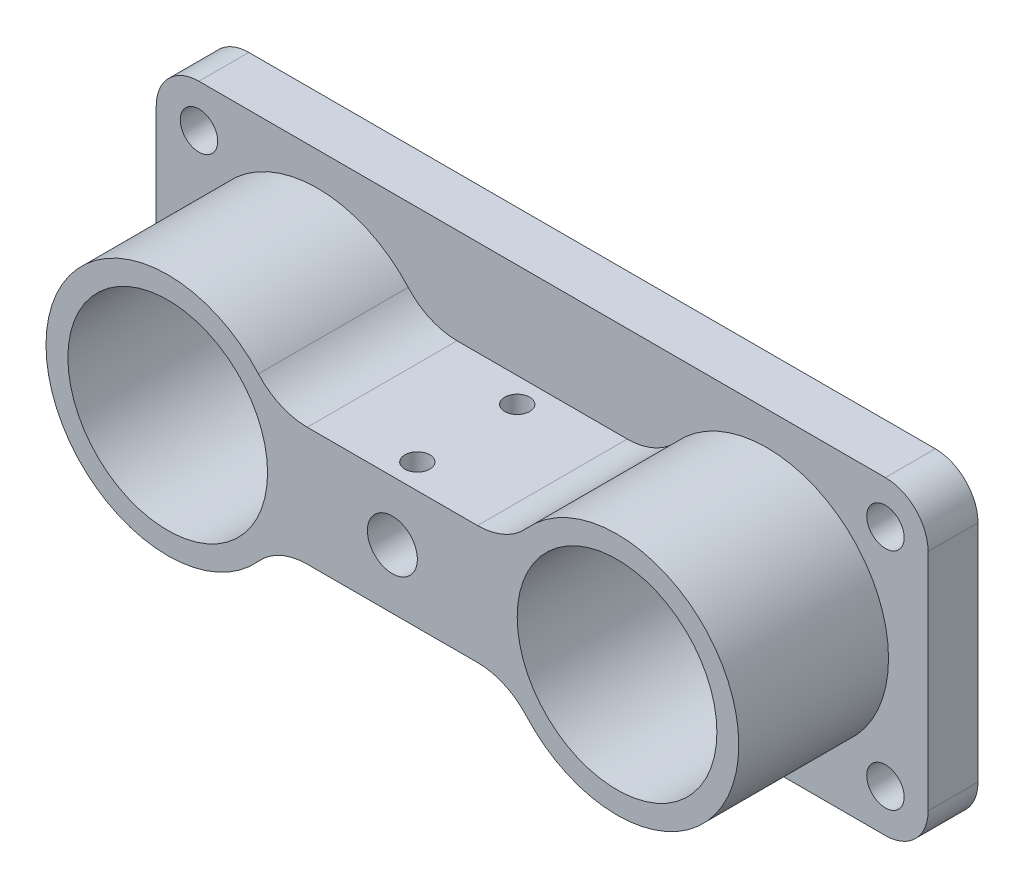
SolidWorks part; units mm, degrees
ref_plane "front" through (0, 0, 0) normal (0, 0, 1) x (1, 0, 0)
ref_plane "top" through (0, 0, 0) normal (0, 1, 0) x (1, 0, 0)
ref_plane "right" through (0, 0, 0) normal (1, 0, 0) x (0, 0, -1)
sketch "Sketch7" plane through (0, 0, 0) normal (0, 0, 1) x (1, 0, 0)
  line L0 (87.3125, 39.4335) -> (-87.3125, 39.4335)
  line L1 (-98.171, 28.575) -> (-98.171, -28.575)
  line L2 (-87.3125, -39.4335) -> (87.3125, -39.4335)
  line L3 (98.171, -28.575) -> (98.171, 28.575)
  line L5 (-85.2165, -36.5641) -> (-79.3394, -30.7654) construction
  line L6 (-79.3394, -30.7654) -> (-81.4227, -22.7763) construction
  line L7 (-81.4227, -22.7763) -> (-89.3831, -20.5859) construction
  line L8 (-89.3831, -20.5859) -> (-95.2602, -26.3846) construction
  line L9 (-95.2602, -26.3846) -> (-93.1769, -34.3737) construction
  line L10 (-93.1769, -34.3737) -> (-85.2165, -36.5641) construction
  arc A0 (87.3125, 39.4335) -> (98.171, 28.575) centre (87.3125, 28.575) cw
  circle A1 centre (-57.15, 0) radius 25.4
  circle A2 centre (-87.2998, -28.575) radius 10.3187 construction
  circle A3 centre (-87.2998, -28.575) radius 7.1501 construction
  arc A4 (-87.3125, 39.4335) -> (-98.171, 28.575) centre (-87.3125, 28.575) ccw
  arc A5 (-98.171, -28.575) -> (-87.3125, -39.4335) centre (-87.3125, -28.575) ccw
  arc A6 (87.3125, -39.4335) -> (98.171, -28.575) centre (87.3125, -28.575) ccw
  circle A8 centre (-87.2998, -28.575) radius 4.7625
  circle A9 centre (-87.2998, 28.575) radius 4.7625
  circle A10 centre (87.3252, -28.575) radius 4.7625
  circle A11 centre (87.3252, 28.575) radius 4.7625
  circle A12 centre (0, 0) radius 6.35
  circle A13 centre (57.15, 0) radius 25.4
  point P26 (98.171, 0)
  point P27 (0, 39.4335)
  dimension "D1" = 10.8585
  dimension "D6" = 50.8
  dimension "D7" = 12.7
  dimension "D12" = 9.525
  dimension "D13" = 20.6375
  dimension "D14" = 14.3002
  dimension "D2" = 196.342
  dimension "D3" = 78.867
  dimension "D4" = 57.15
  dimension "D5" = 57.15
  dimension "D8" = 87.3252
  dimension "D9" = 174.625
  dimension "D10" = 28.575
  dimension "D11" = 57.15
  dimension "D15" = 185.4835
  dimension "D16" = 10.8585
sketch "Sketch1" plane through (0, 0, 0) normal (0, 0, 1) x (1, 0, 0)
  line L12 (99.7585, -28.575) -> (99.7585, 28.575)
  line L13 (87.3125, 41.021) -> (-87.3125, 41.021)
  line L14 (-99.7585, 28.575) -> (-99.7585, -28.575)
  line L15 (-87.3125, -41.021) -> (87.3125, -41.021)
  line L16 (99.7585, -28.575) -> (99.7585, 28.575)
  line L17 (87.3125, 41.021) -> (-87.3125, 41.021)
  line L18 (-99.7585, 28.575) -> (-99.7585, -28.575)
  line L19 (-87.3125, -41.021) -> (87.3125, -41.021)
  arc A18 (99.7585, 28.575) -> (87.3125, 41.021) centre (87.3125, 28.575) ccw
  arc A19 (-87.3125, 41.021) -> (-99.7585, 28.575) centre (-87.3125, 28.575) ccw
  arc A20 (-99.7585, -28.575) -> (-87.3125, -41.021) centre (-87.3125, -28.575) ccw
  arc A21 (87.3125, -41.021) -> (99.7585, -28.575) centre (87.3125, -28.575) ccw
  arc A22 (99.7585, 28.575) -> (87.3125, 41.021) centre (87.3125, 28.575) ccw
  arc A23 (-87.3125, 41.021) -> (-99.7585, 28.575) centre (-87.3125, 28.575) ccw
  arc A24 (-99.7585, -28.575) -> (-87.3125, -41.021) centre (-87.3125, -28.575) ccw
  arc A25 (87.3125, -41.021) -> (99.7585, -28.575) centre (87.3125, -28.575) ccw
  dimension "D1" = 1.5875
extrude "Base-Extrude" add sketch "Sketch1" against normal blind 50.8 draft 3
sketch "Sketch8" plane through (0, 0, 0) normal (0, 0, 1) x (1, 0, 0)
  line L0 (25.2111, 29.9085) -> (-25.2111, 29.9085)
  line L1 (-25.2111, -29.9085) -> (25.2111, -29.9085)
  line L2 (87.3125, 39.4335) -> (-87.3125, 39.4335) construction
  line L3 (-87.3125, -39.4335) -> (87.3125, -39.4335) construction
  line L4 (25.2111, 23.5585) -> (-0.1889, 23.5585) construction
  arc A0 (25.2111, -29.9085) -> (30.3213, -19.7891) centre (25.2111, -23.5585) ccw
  arc A1 (25.2111, 29.9085) -> (30.3213, 19.7891) centre (25.2111, 23.5585) cw
  arc A2 (-25.2111, 29.9085) -> (-30.3213, 19.7891) centre (-25.2111, 23.5585) ccw
  arc A3 (-25.2111, -29.9085) -> (-30.3213, -19.7891) centre (-25.2111, -23.5585) cw
  circle A4 centre (0, 0) radius 12.7 construction
  arc A6 (30.3213, 19.7891) -> (30.3213, -19.7891) centre (57.15, 0) ccw
  arc A7 (-30.3213, -19.7891) -> (-30.3213, 19.7891) centre (-57.15, 0) ccw
  dimension "D3" = 66.675
  dimension "D4" = 66.675
  dimension "D5" = 6.35
  dimension "D6" = 25.4
  dimension "D1" = 9.525
  dimension "D2" = 9.525
  dimension "D7" = 25.4
sketch "Sketch17" plane through (0, 0, 0) normal (0, 0, 1) x (1, 0, 0)
  line L0 (25.2111, 23.5585) -> (-0.1889, 23.5585) construction
  line L1 (-25.2111, -29.9085) -> (25.2111, -29.9085) construction
  line L2 (25.2111, 29.9085) -> (-25.2111, 29.9085) construction
  line L3 (25.2111, 23.5585) -> (-0.1889, 23.5585) construction
  line L4 (-25.2111, -29.9085) -> (25.2111, -29.9085)
  line L5 (25.2111, 29.9085) -> (-25.2111, 29.9085)
  line L6 (98.171, -28.575) -> (98.171, 28.575) construction
  line L7 (87.3125, 39.4335) -> (-87.3125, 39.4335) construction
  line L8 (98.171, -28.575) -> (98.171, 28.575)
  line L9 (87.3125, 39.4335) -> (-87.3125, 39.4335)
  line L10 (-25.3525, -20.3835) -> (19.4445, -20.3835) construction
  circle A0 centre (0, 0) radius 12.7 construction
  arc A1 (30.3213, 19.7891) -> (25.2111, 29.9085) centre (25.2111, 23.5585) ccw construction
  arc A2 (30.3213, 19.7891) -> (30.3213, -19.7891) centre (57.15, 0) ccw construction
  arc A3 (25.2111, -29.9085) -> (30.3213, -19.7891) centre (25.2111, -23.5585) ccw construction
  arc A4 (-30.3213, -19.7891) -> (-25.2111, -29.9085) centre (-25.2111, -23.5585) ccw construction
  arc A5 (-30.3213, -19.7891) -> (-30.3213, 19.7891) centre (-57.15, 0) ccw construction
  arc A6 (-25.2111, 29.9085) -> (-30.3213, 19.7891) centre (-25.2111, 23.5585) ccw construction
  circle A7 centre (0, 0) radius 12.7 construction
  arc A8 (30.3213, 19.7891) -> (25.2111, 29.9085) centre (25.2111, 23.5585) ccw
  arc A9 (30.3213, 19.7891) -> (30.3213, -19.7891) centre (57.15, 0) ccw
  arc A10 (25.2111, -29.9085) -> (30.3213, -19.7891) centre (25.2111, -23.5585) ccw
  arc A11 (-30.3213, -19.7891) -> (-25.2111, -29.9085) centre (-25.2111, -23.5585) ccw
  arc A12 (-30.3213, -19.7891) -> (-30.3213, 19.7891) centre (-57.15, 0) ccw
  arc A13 (-25.2111, 29.9085) -> (-30.3213, 19.7891) centre (-25.2111, 23.5585) ccw
  circle A14 centre (0, 0) radius 22.225 construction
  arc A15 (22.8087, 25.6489) -> (19.4445, -20.3835) centre (57.15, 0) ccw construction
  circle A16 centre (0, 0) radius 17.4752
  point P23 (0, -12.7)
  point P24 (0, -22.225)
  point P28 (0, -17.4752)
  point P30 (0, 17.4752)
  dimension "D7" = 6.35
  dimension "D8" = 33.3375
  dimension "D1" = 72.9599
  dimension "D2" = 15.875
  dimension "D3" = 9.525
  dimension "D4" = 67.8497
  dimension "D5" = 15.875
  dimension "D6" = 123.3821
  dimension "D9" = 59.2226
  dimension "D10" = 69.342
  dimension "D11" = 26.8287
  dimension "D12" = 19.7891
  dimension "D13" = 19.6444
  dimension "D14" = 9.525
  dimension "D17" = 98.3599
  dimension "D18" = 128.4923
  dimension "D19" = 3.7694
  dimension "D20" = 5.1102
  dimension "D21" = 6.35
  dimension "D22" = 6.35
  dimension "D23" = 3.7694
  dimension "D24" = 4.7752
  dimension "D25" = 21.9583
  dimension "D26" = 17.4752
  dimension "D15" = 9.525
  dimension "D16" = 9.525
sketch "Sketch2" plane through (0, 0, 0) normal (0, 0, 1) x (1, 0, 0)
  line L0 (0, -2.2818) -> (0, 10.4027) construction
  line L1 (-10.1716, 0) -> (10.1716, 0) construction
  line L2 (-21.6524, 19.05) -> (21.6524, 19.05)
  line L3 (-21.6524, -19.05) -> (21.6524, -19.05)
  line L4 (-99.2711, -9.525) -> (-116.0701, -9.525) construction
  line L5 (-99.2711, 9.525) -> (-116.0701, 9.525) construction
  line L6 (99.2711, -9.525) -> (116.0701, -9.525) construction
  line L7 (99.2711, 9.525) -> (116.0701, 9.525) construction
  line L9 (-124.922, 63.0143) -> (120.2967, 63.0143)
  line L10 (-124.922, 63.0143) -> (-124.922, -70.9973)
  line L11 (-124.922, -70.9973) -> (120.2967, -70.9973)
  line L12 (120.2967, 63.0143) -> (120.2967, -70.9973)
  arc A0 (31.1184, -23.2833) -> (31.1184, 23.2833) centre (57.15, 0) ccw
  arc A1 (-31.1184, 23.2833) -> (-31.1184, -23.2833) centre (-57.15, 0) ccw
  circle A2 centre (0, 0) radius 15.875 construction
  circle A3 centre (0, 0) radius 8.7376 construction
  circle A4 centre (15.4813, 0) radius 6.7437 construction
  arc A5 (21.6524, 19.05) -> (31.1184, 23.2833) centre (21.6524, 31.75) ccw
  arc A6 (-21.6524, 19.05) -> (-31.1184, 23.2833) centre (-21.6524, 31.75) cw
  arc A7 (-21.6524, -19.05) -> (-31.1184, -23.2833) centre (-21.6524, -31.75) ccw
  arc A8 (21.6524, -19.05) -> (31.1184, -23.2833) centre (21.6524, -31.75) cw
  circle A9 centre (-87.2998, -28.575) radius 10.3188 construction
  circle A10 centre (-87.2998, -28.575) radius 10.3187 construction
  arc A11 (-87.207, -18.2567) -> (-99.2711, -9.525) centre (-99.2711, -22.225) ccw construction
  arc A12 (-88.0388, 16.2983) -> (-99.2711, 9.525) centre (-99.2711, 22.225) cw construction
  arc A13 (87.207, -18.2567) -> (99.2711, -9.525) centre (99.2711, -22.225) cw construction
  arc A14 (88.0388, 16.2983) -> (99.2711, 9.525) centre (99.2711, 22.225) ccw construction
  dimension "D1" = 69.85
  dimension "D2" = 31.75
  dimension "D3" = 17.4752
  dimension "D4" = 13.4874
  dimension "D5" = 12.7
  dimension "D7" = 25.4
  dimension "D6" = 38.1
  dimension "D8" = 19.05
extrude "Cut-Extrude5" cut sketch "Sketch2" against normal blind 38.1 draft 5
sketch "Sketch3" plane through (0, 0, -50.8) normal (0, 0, -1) x (-1, 0, 0)
  circle A0 centre (57.15, 0) radius 24.6062
  circle A1 centre (-57.15, 0) radius 24.6062
  dimension "D1" = 49.2125
extrude "Cut-Extrude1" cut sketch "Sketch3" against normal through all draft 5
sketch "Sketch5" plane through (0, 0, 0) normal (0, 0, 1) x (1, 0, 0)
  line L4 (98.171, -28.575) -> (98.171, 28.575) construction
  line L5 (108.5492, 51.5785) -> (-109.2526, 51.5785)
  line L6 (108.5492, 51.5785) -> (108.5492, -63.3009)
  line L7 (108.5492, -63.3009) -> (-109.2526, -63.3009)
  line L8 (-87.3125, -39.4335) -> (87.3125, -39.4335) construction
  line L9 (-98.171, 28.575) -> (-98.171, -28.575) construction
  line L10 (87.3125, 39.4335) -> (-87.3125, 39.4335) construction
  line L11 (98.171, -28.575) -> (98.171, 28.575)
  line L12 (-87.3125, -39.4335) -> (87.3125, -39.4335)
  line L13 (-98.171, 28.575) -> (-98.171, -28.575)
  line L14 (87.3125, 39.4335) -> (-87.3125, 39.4335)
  line L16 (-109.2526, 51.5785) -> (-109.2526, -63.3009)
  arc A4 (98.171, 28.575) -> (87.3125, 39.4335) centre (87.3125, 28.575) ccw construction
  arc A5 (87.3125, -39.4335) -> (98.171, -28.575) centre (87.3125, -28.575) ccw construction
  arc A6 (-98.171, -28.575) -> (-87.3125, -39.4335) centre (-87.3125, -28.575) ccw construction
  arc A7 (-87.3125, 39.4335) -> (-98.171, 28.575) centre (-87.3125, 28.575) ccw construction
  arc A8 (98.171, 28.575) -> (87.3125, 39.4335) centre (87.3125, 28.575) ccw
  arc A9 (87.3125, -39.4335) -> (98.171, -28.575) centre (87.3125, -28.575) ccw
  arc A10 (-98.171, -28.575) -> (-87.3125, -39.4335) centre (-87.3125, -28.575) ccw
  arc A11 (-87.3125, 39.4335) -> (-98.171, 28.575) centre (-87.3125, 28.575) ccw
  dimension "D1" = 196.342
extrude "Mill outside" cut sketch "Sketch5" against normal through all
sketch "Sketch9" plane through (0, 0, 0) normal (0, 0, 1) x (1, 0, 0)
  line L0 (-32.9819, 33.0835) -> (32.9819, 33.0835) construction
  line L1 (41.021, 41.1226) -> (32.9819, 33.0835) construction
  line L2 (98.171, -28.575) -> (98.171, 28.575) construction
  line L3 (-105.3164, 60.2662) -> (122.7394, 60.2662)
  line L4 (-21.6524, -15.0876) -> (21.6524, -15.0876)
  line L5 (21.6524, 15.0876) -> (-21.6524, 15.0876)
  line L6 (-21.6524, -15.0876) -> (21.6524, -15.0876)
  line L7 (21.6524, 15.0876) -> (-21.6524, 15.0876)
  line L8 (-105.3164, 60.2662) -> (-105.3164, -51.7346)
  line L9 (-105.3164, -51.7346) -> (122.7394, -51.7346)
  line L10 (122.7394, 60.2662) -> (122.7394, -51.7346)
  line L11 (87.3125, 39.4335) -> (-87.3125, 39.4335) construction
  line L12 (98.171, -22.0726) -> (98.171, 39.4335) construction
  line L13 (100.6408, 39.4335) -> (-87.3125, 39.4335) construction
  line L14 (41.021, 41.1226) -> (79.121, 41.1226) construction
  line L15 (0, 10.2862) -> (0, -7.0133) construction
  line L16 (-10.8706, 0) -> (10.6368, 0) construction
  line L17 (-41.021, 41.1226) -> (-79.121, 41.1226) construction
  line L18 (-41.021, 41.1226) -> (-32.9819, 33.0835) construction
  line L19 (-41.021, -41.1226) -> (-79.121, -41.1226) construction
  line L20 (-41.021, -41.1226) -> (-32.9819, -33.0835) construction
  line L21 (-32.9819, -33.0835) -> (32.9819, -33.0835) construction
  line L22 (41.021, -41.1226) -> (32.9819, -33.0835) construction
  line L23 (41.021, -41.1226) -> (79.121, -41.1226) construction
  circle A0 centre (-87.2998, -28.575) radius 10.3188 construction
  circle A1 centre (-87.2998, -28.575) radius 10.3187 construction
  arc A2 (98.171, 22.0726) -> (79.121, 41.1226) centre (79.121, 22.0726) ccw construction
  arc A4 (-98.171, 22.0726) -> (-79.121, 41.1226) centre (-79.121, 22.0726) cw construction
  arc A5 (-98.171, -22.0726) -> (-79.121, -41.1226) centre (-79.121, -22.0726) ccw construction
  arc A6 (98.171, -22.0726) -> (79.121, -41.1226) centre (79.121, -22.0726) cw construction
  arc A14 (-34.0718, 20.6417) -> (-34.0718, -20.6417) centre (-57.15, 0) ccw
  arc A15 (-21.6524, -15.0876) -> (-34.0718, -20.6417) centre (-21.6524, -31.75) ccw
  arc A16 (34.0718, -20.6417) -> (21.6524, -15.0876) centre (21.6524, -31.75) ccw
  arc A17 (34.0718, -20.6417) -> (34.0718, 20.6417) centre (57.15, 0) ccw
  arc A18 (21.6524, 15.0876) -> (34.0718, 20.6417) centre (21.6524, 31.75) ccw
  arc A19 (-34.0718, 20.6417) -> (-21.6524, 15.0876) centre (-21.6524, 31.75) ccw
  arc A20 (-34.0718, 20.6417) -> (-34.0718, -20.6417) centre (-57.15, 0) ccw
  arc A21 (-21.6524, -15.0876) -> (-34.0718, -20.6417) centre (-21.6524, -31.75) ccw
  arc A22 (34.0718, -20.6417) -> (21.6524, -15.0876) centre (21.6524, -31.75) ccw
  arc A23 (34.0718, -20.6417) -> (34.0718, 20.6417) centre (57.15, 0) ccw
  arc A24 (21.6524, 15.0876) -> (34.0718, 20.6417) centre (21.6524, 31.75) ccw
  arc A25 (-34.0718, 20.6417) -> (-21.6524, 15.0876) centre (-21.6524, 31.75) ccw
  point P12 (41.021, 26.4299)
  point P34 (88.1126, 0)
  point P35 (57.15, 30.9626)
  dimension "D1" = 3.9624
  dimension "D2" = 30.9626
  dimension "D3" = 57.15
  dimension "D6" = 19.05
  dimension "D19" = 177.292
  dimension "D23" = 19.05
  dimension "D4" = 10.16
  dimension "D5" = 10.0584
  dimension "D7" = 6.35
  dimension "D8" = 135
  dimension "D9" = 57.15
  dimension "D10" = 1.6891
  dimension "D11" = 19.05
  dimension "D12" = 17.3609
  dimension "D13" = 65.1891
  dimension "D14" = 131.1529
  dimension "D15" = 139.192
  dimension "D16" = 61.5061
  dimension "D17" = 80.5561
  dimension "D18" = 72.517
  dimension "D20" = 196.342
  dimension "D21" = 41.021
  dimension "D22" = 8.4709
  dimension "D25" = 24.3459
extrude "Mill boss" cut sketch "Sketch9" against normal up to surface (38.1 mm away)
sketch "Sketch4" plane through (0, 0, -50.8) normal (0, 0, -1) x (-1, 0, 0)
  circle A3 centre (-57.15, 0) radius 25.4 construction
  circle A4 centre (0, 0) radius 6.35 construction
  circle A5 centre (57.15, 0) radius 25.4 construction
  circle A6 centre (-87.3252, 28.575) radius 4.7625 construction
  circle A7 centre (-87.3252, -28.575) radius 4.7625 construction
  circle A8 centre (87.2998, -28.575) radius 4.7625 construction
  circle A9 centre (87.2998, 28.575) radius 4.7625 construction
  circle A10 centre (-57.15, 0) radius 25.4
  circle A11 centre (57.15, 0) radius 25.4
  circle A12 centre (0, 0) radius 6.35
  circle A13 centre (-87.3252, 28.575) radius 4.7625
  circle A14 centre (-87.3252, -28.575) radius 4.7625
  circle A15 centre (87.2998, -28.575) radius 4.7625
  circle A16 centre (87.2998, 28.575) radius 4.7625
  dimension "D1" = 12.7
  dimension "D2" = 50.8
extrude "Bores and holes" cut sketch "Sketch4" against normal through all
sketch "Sketch18" plane through (0, 0, 0) normal (0, 1, 0) x (1, 0, 0)
  line L0 (0, 0) -> (0, 50.8) construction
  line L2 (87.3125, 50.8) -> (-87.3125, 50.8) construction
  circle A0 centre (0, 6.35) radius 3.175
  circle A1 centre (0, 31.75) radius 3.175
  dimension "D1" = 6.35
  dimension "D2" = 6.35
  dimension "D3" = 25.4
  dimension "D4" = 19.05
extrude "Set screw holes" cut sketch "Sketch18" along normal blind 38.1
sketch "Sketch19" plane through (0, 0, 0) normal (0, 0, 1) x (1, 0, 0)
  line L0 (-21.6524, -15.0876) -> (21.6524, -15.0876) construction
  line L1 (21.6524, 15.0876) -> (-21.6524, 15.0876) construction
  line L2 (-21.6524, -15.0876) -> (21.6524, -15.0876)
  line L3 (21.6524, 15.0876) -> (-21.6524, 15.0876)
  line L4 (100.6408, 39.4335) -> (-87.3125, 39.4335) construction
  line L5 (98.171, -22.0726) -> (98.171, 39.4335) construction
  line L6 (100.6408, 39.4335) -> (-87.3125, 39.4335)
  line L7 (98.171, -22.0726) -> (98.171, 39.4335)
  line L8 (122.7394, 60.2662) -> (-105.3164, 60.2662)
  line L9 (122.7394, -51.7346) -> (122.7394, 60.2662)
  line L10 (-105.3164, -51.7346) -> (122.7394, -51.7346)
  line L11 (-105.3164, 60.2662) -> (-105.3164, -51.7346)
  line L12 (122.7394, 60.2662) -> (-105.3164, 60.2662)
  line L13 (122.7394, -51.7346) -> (122.7394, 60.2662)
  line L14 (-105.3164, -51.7346) -> (122.7394, -51.7346)
  line L15 (-105.3164, 60.2662) -> (-105.3164, -51.7346)
  line L16 (122.7394, 60.2662) -> (-105.3164, 60.2662)
  line L17 (122.7394, -51.7346) -> (122.7394, 60.2662)
  line L18 (-105.3164, -51.7346) -> (122.7394, -51.7346)
  line L19 (-105.3164, 60.2662) -> (-105.3164, -51.7346)
  line L20 (122.7394, 60.2662) -> (-105.3164, 60.2662)
  line L21 (122.7394, -51.7346) -> (122.7394, 60.2662)
  line L22 (-105.3164, -51.7346) -> (122.7394, -51.7346)
  line L23 (-105.3164, 60.2662) -> (-105.3164, -51.7346)
  arc A0 (34.0718, -20.6417) -> (21.6524, -15.0876) centre (21.6524, -31.75) ccw construction
  arc A1 (-21.6524, -15.0876) -> (-34.0718, -20.6417) centre (-21.6524, -31.75) ccw construction
  arc A2 (-34.0718, 20.6417) -> (-34.0718, -20.6417) centre (-57.15, 0) ccw construction
  arc A3 (-34.0718, 20.6417) -> (-21.6524, 15.0876) centre (-21.6524, 31.75) ccw construction
  arc A4 (21.6524, 15.0876) -> (34.0718, 20.6417) centre (21.6524, 31.75) ccw construction
  arc A5 (34.0718, -20.6417) -> (34.0718, 20.6417) centre (57.15, 0) ccw construction
  arc A6 (34.0718, -20.6417) -> (21.6524, -15.0876) centre (21.6524, -31.75) ccw
  arc A7 (-21.6524, -15.0876) -> (-34.0718, -20.6417) centre (-21.6524, -31.75) ccw
  arc A8 (-34.0718, 20.6417) -> (-34.0718, -20.6417) centre (-57.15, 0) ccw
  arc A9 (-34.0718, 20.6417) -> (-21.6524, 15.0876) centre (-21.6524, 31.75) ccw
  arc A10 (21.6524, 15.0876) -> (34.0718, 20.6417) centre (21.6524, 31.75) ccw
  arc A11 (34.0718, -20.6417) -> (34.0718, 20.6417) centre (57.15, 0) ccw
  point P18 (57.15, 30.9626)
  point P19 (41.021, 26.4299)
  dimension "D14" = 20.6417
  dimension "D3" = 8.4709
  dimension "D4" = 41.021
  dimension "D5" = 60.0752
  dimension "D6" = 54.5211
  dimension "D7" = 24.3459
  dimension "D8" = 18.7918
  dimension "D9" = 30.9626
  dimension "D10" = 12.4194
  dimension "D11" = 11.1083
  dimension "D12" = 20.6417
  dimension "D13" = 23.0782
  dimension "D15" = 23.0782
  dimension "D16" = 64.0992
  dimension "D17" = 76.5186
  dimension "D18" = 119.8234
  dimension "D19" = 132.2428
  dimension "D20" = 16.6624
  dimension "D21" = 16.6624
  dimension "D22" = 57.15
  dimension "D23" = 13.0036
  dimension "D24" = 39.4335
  dimension "D1" = 0
  dimension "D2" = 0
sketch "Sketch20" plane through (0, 0, 0) normal (0, 0, 1) x (1, 0, 0)
  line L0 (-98.171, 28.575) -> (-98.171, -28.575) construction
  line L1 (-87.3125, -39.4335) -> (87.3125, -39.4335) construction
  line L2 (98.171, -28.575) -> (98.171, 28.575) construction
  line L3 (87.3125, 39.4335) -> (-87.3125, 39.4335) construction
  line L4 (-98.171, 28.575) -> (-98.171, -28.575)
  line L5 (-87.3125, -39.4335) -> (87.3125, -39.4335)
  line L6 (98.171, -28.575) -> (98.171, 28.575)
  line L7 (87.3125, 39.4335) -> (-87.3125, 39.4335)
  line L8 (99.2251, 41.275) -> (-99.2251, -41.275) construction
  line L9 (-99.2251, 41.275) -> (99.2251, 41.275)
  line L10 (-99.2251, 41.275) -> (-99.2251, -41.275)
  line L11 (-99.2251, -41.275) -> (99.2251, -41.275)
  line L12 (99.2251, 41.275) -> (99.2251, -41.275)
  arc A0 (-87.3125, 39.4335) -> (-98.171, 28.575) centre (-87.3125, 28.575) ccw construction
  arc A1 (-98.171, -28.575) -> (-87.3125, -39.4335) centre (-87.3125, -28.575) ccw construction
  arc A2 (87.3125, -39.4335) -> (98.171, -28.575) centre (87.3125, -28.575) ccw construction
  arc A3 (98.171, 28.575) -> (87.3125, 39.4335) centre (87.3125, 28.575) ccw construction
  arc A4 (-87.3125, 39.4335) -> (-98.171, 28.575) centre (-87.3125, 28.575) ccw
  arc A5 (-98.171, -28.575) -> (-87.3125, -39.4335) centre (-87.3125, -28.575) ccw
  arc A6 (87.3125, -39.4335) -> (98.171, -28.575) centre (87.3125, -28.575) ccw
  arc A7 (98.171, 28.575) -> (87.3125, 39.4335) centre (87.3125, 28.575) ccw
  circle A8 centre (87.3252, -28.575) radius 4.7625 construction
  circle A9 centre (87.3252, 28.575) radius 4.7625 construction
  circle A10 centre (0, 0) radius 6.35 construction
  circle A11 centre (-87.2998, -28.575) radius 4.7625 construction
  circle A12 centre (-87.2998, 28.575) radius 4.7625 construction
  circle A13 centre (87.3252, -28.575) radius 4.7625
  circle A14 centre (87.3252, 28.575) radius 4.7625
  circle A15 centre (0, 0) radius 6.35
  circle A16 centre (-87.2998, -28.575) radius 4.7625
  circle A17 centre (-87.2998, 28.575) radius 4.7625
  circle A18 centre (57.15, 0) radius 25.4 construction
  circle A19 centre (-57.15, 0) radius 25.4 construction
  circle A20 centre (57.15, 0) radius 25.4
  circle A21 centre (-57.15, 0) radius 25.4
  dimension "D9" = 10.8585
  dimension "D12" = 11.8999
  dimension "D13" = 186.5249
  dimension "D14" = 12.7
  dimension "D20" = 39.4335
  dimension "D22" = 41.021
  dimension "D23" = 155.321
  dimension "D1" = 198.4502
  dimension "D2" = 1.0541
  dimension "D3" = 82.55
  dimension "D4" = 1.8415
  dimension "D5" = 80.7085
  dimension "D6" = 12.7
  dimension "D7" = 69.85
  dimension "D8" = 11.9126
  dimension "D10" = 197.3961
  dimension "D11" = 186.5376
  dimension "D15" = 69.85
  dimension "D16" = 41.275
  dimension "D17" = 99.2251
  dimension "D18" = 42.0751
  dimension "D19" = 156.3751
  dimension "D21" = 98.171
